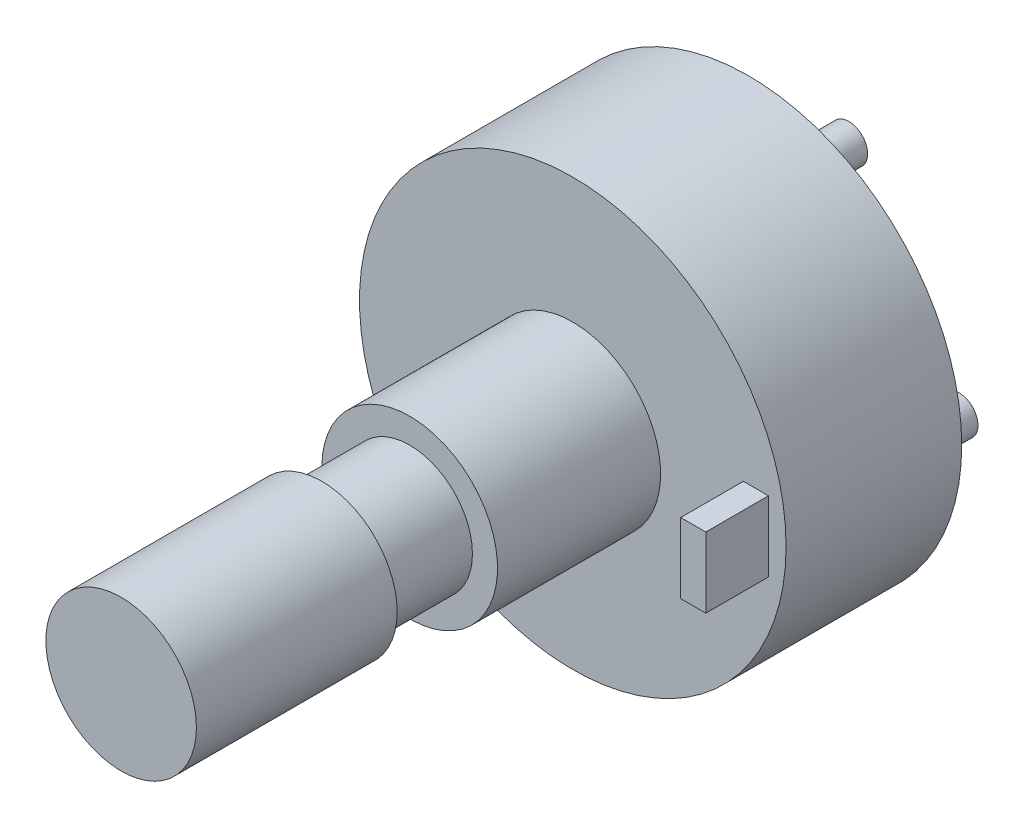
SolidWorks part; units mm, degrees
ref_plane "Спереди" through (0, 0, 0) normal (0, 0, 1) x (1, 0, 0)
ref_plane "Сверху" through (0, 0, 0) normal (0, 1, 0) x (1, 0, 0)
ref_plane "Справа" through (0, 0, 0) normal (1, 0, 0) x (0, 0, -1)
sketch "Эскиз1" plane through (0, 0, 0) normal (0, 0, 1) x (1, 0, 0)
  circle A0 centre (0, 0) radius 8.5
  dimension "D1" = 17
extrude "Вытянуть1" add sketch "Эскиз1" along normal blind 7
sketch "Эскиз2" plane through (0, 0, 7) normal (0, 0, 1) x (1, 0, 0)
  line L2 (-7.5, 4) -> (7.5, 4)
  line L3 (-7.5, 4) -> (-7.5, 12.5)
  line L4 (-7.5, 12.5) -> (7.5, 12.5)
  line L5 (7.5, 4) -> (7.5, 12.5)
  circle A0 centre (0, 0) radius 8.5 construction
  dimension "D1" = 15
  dimension "D2" = 12.5
extrude "Вытянуть2" [suppressed] add sketch "Эскиз2" against normal blind 1
sketch "Эскиз3" [suppressed] plane through (0, 0, 6) normal (0, 0, -1) x (-1, 0, 0)
  line L0 (0, 0) -> (0, 18.8831) construction
  line L1 (-7.5, 12.5) -> (7.5, 12.5) construction
  line L2 (-0.6, 10.5) -> (0.6, 10.5)
  line L3 (-0.6, 10.5) -> (-0.6, 16.5)
  line L4 (-0.6, 16.5) -> (0.6, 16.5)
  line L5 (0.6, 10.5) -> (0.6, 16.5)
  line L6 (-5.6, 10.497) -> (-4.4, 10.497)
  line L7 (-5.6, 10.497) -> (-5.6, 16.497)
  line L8 (-5.6, 16.497) -> (-4.4, 16.497)
  line L9 (-4.4, 10.497) -> (-4.4, 16.497)
  line L10 (4.4, 10.497) -> (5.6, 10.497)
  line L11 (4.4, 10.497) -> (4.4, 16.497)
  line L12 (4.4, 16.497) -> (5.6, 16.497)
  line L13 (5.6, 10.497) -> (5.6, 16.497)
  dimension "D1" = 1.2
  dimension "D2" = 4
  dimension "D3" = 6
  dimension "D4" = 5
  dimension "D5" = 5
extrude "Вытянуть3" [suppressed] add sketch "Эскиз3" along normal blind 0.8
sketch "Эскиз4" plane through (0, 0, 7) normal (0, 0, 1) x (1, 0, 0)
  line L0 (-7.5553, 0) -> (10.2523, 0) construction
  line L1 (0, 0) -> (0, 7.584) construction
  line L6 (6.8, 1.4) -> (7.8, 1.4)
  line L7 (6.8, -1.4) -> (7.8, -1.4)
  line L8 (6.8, -1.4) -> (6.8, 1.4)
  line L10 (7.8, -1.4) -> (7.8, 1.4)
  circle A0 centre (0, 0) radius 8.5 construction
  dimension "D5" = 7.8
  dimension "D4" = 1
extrude "Вытянуть4" add sketch "Эскиз4" along normal blind 2.5
sketch "Эскиз5" plane through (0, 0, 7) normal (0, 0, 1) x (1, 0, 0)
  circle A0 centre (0, 0) radius 3.5
  dimension "D1" = 7
extrude "Вытянуть5" add sketch "Эскиз5" along normal blind 6.5
sketch "Эскиз6" plane through (0, 0, 13.5) normal (0, 0, 1) x (1, 0, 0)
  circle A0 centre (0, 0) radius 2.5
  dimension "D1" = 5
extrude "Вытянуть6" add sketch "Эскиз6" along normal blind 3.5
sketch "Эскиз7" plane through (0, 0, 17) normal (0, 0, 1) x (1, 0, 0)
  circle A0 centre (0, 0) radius 3
  point P3 (0, 0)
  dimension "D1" = 6
extrude "Вытянуть7" add sketch "Эскиз7" along normal blind 8
sketch "Эскиз8" plane through (0, 0, 0) normal (0, 0, -1) x (-1, 0, 0)
  line L0 (0, 9.1002) -> (0, -9.1012) construction
  line L1 (-5.3846, -2.9962) -> (5.7258, -2.9962) construction
  circle A0 centre (0, 4.1706) radius 0.75
  circle A1 centre (4.3987, -2.9962) radius 0.75
  circle A2 centre (-4.3987, -2.9962) radius 0.75
  dimension "D1" = 1.5
extrude "Вытянуть8" add sketch "Эскиз8" along normal blind 4
sketch "Эскиз9" plane through (0, 0, 0) normal (0, 0, -1) x (-1, 0, 0)
  text T0 "1" font "GOST type B" height 2
  text T1 "2" font "GOST type B" height 2
  text T2 "3" font "GOST type B" height 2
extrude "Вырез-Вытянуть1" cut sketch "Эскиз9" against normal blind 0.1
